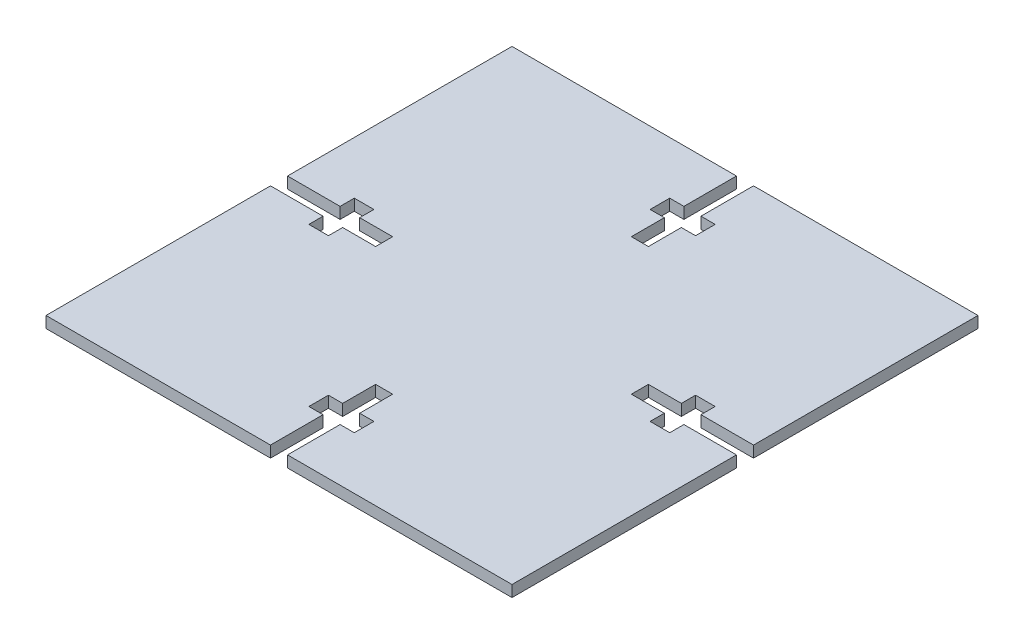
SolidWorks part; units mm, degrees
ref_plane "Front Plane" through (0, 0, 0) normal (0, 0, 1) x (1, 0, 0)
ref_plane "Top Plane" through (0, 0, 0) normal (0, 1, 0) x (1, 0, 0)
ref_plane "Right Plane" through (0, 0, 0) normal (1, 0, 0) x (0, 0, -1)
sketch "Sketch1" plane through (0, 0, 0) normal (0, 1, 0) x (1, 0, 0)
  line L1 (-41, -41) -> (41, -41)
  line L2 (-41, -41) -> (-41, 41)
  line L3 (-41, 41) -> (41, 41)
  line L4 (41, -41) -> (41, 41)
  line L5 (-41, -41) -> (41, 41) construction
  line L6 (-41, 41) -> (41, -41) construction
  point P0 (0, 0)
  dimension "D1" = 82
  dimension "D2" = 82
extrude "Boss-Extrude1" add sketch "Sketch1" along normal blind 2
sketch "Sketch2" plane through (0, 0, 0) normal (0, -1, 0) x (-1, 0, 0)
  line L0 (0, 41) -> (0, -41) construction
  line L1 (-41, 41) -> (41, 41) construction
  line L2 (41, -41) -> (-41, -41) construction
  line L4 (-1.5, 22.5) -> (1.5, 22.5)
  line L5 (-1.5, 22.5) -> (-1.5, 28.3)
  line L6 (-1.5, 41) -> (1.5, 41)
  line L7 (1.5, 22.5) -> (1.5, 28.3)
  line L8 (-1.5, 22.5) -> (1.5, 41) construction
  line L9 (-1.5, 41) -> (1.5, 22.5) construction
  line L10 (4, 28.3) -> (1.5, 28.3)
  line L11 (4, 28.3) -> (4, 31.75)
  line L12 (4, 31.75) -> (1.5, 31.75)
  line L13 (-4, 28.3) -> (-4, 31.75)
  line L14 (4, 28.3) -> (-4, 31.75) construction
  line L15 (4, 31.75) -> (-4, 28.3) construction
  line L39 (1.5, 31.75) -> (1.5, 41)
  line L40 (-1.5, 31.75) -> (-4, 31.75)
  line L41 (-1.5, 31.75) -> (-1.5, 41)
  line L42 (-1.5, 28.3) -> (-4, 28.3)
  line L43 (28.3, -4) -> (28.3, -1.5)
  line L44 (22.5, -1.5) -> (28.3, -1.5)
  line L45 (22.5, 1.5) -> (22.5, -1.5)
  line L46 (22.5, 1.5) -> (28.3, 1.5)
  line L47 (28.3, 1.5) -> (28.3, 4)
  line L48 (28.3, 4) -> (31.75, 4)
  line L49 (31.75, 1.5) -> (31.75, 4)
  line L50 (31.75, 1.5) -> (41, 1.5)
  line L51 (41, 1.5) -> (41, -1.5)
  line L52 (31.75, -1.5) -> (41, -1.5)
  line L53 (31.75, -4) -> (31.75, -1.5)
  line L54 (28.3, -4) -> (31.75, -4)
  line L55 (-4, -28.3) -> (-1.5, -28.3)
  line L56 (-1.5, -22.5) -> (-1.5, -28.3)
  line L57 (1.5, -22.5) -> (-1.5, -22.5)
  line L58 (1.5, -22.5) -> (1.5, -28.3)
  line L59 (1.5, -28.3) -> (4, -28.3)
  line L60 (4, -28.3) -> (4, -31.75)
  line L61 (1.5, -31.75) -> (4, -31.75)
  line L62 (1.5, -31.75) -> (1.5, -41)
  line L63 (1.5, -41) -> (-1.5, -41)
  line L64 (-1.5, -31.75) -> (-1.5, -41)
  line L65 (-4, -31.75) -> (-1.5, -31.75)
  line L66 (-4, -28.3) -> (-4, -31.75)
  line L67 (-28.3, 4) -> (-28.3, 1.5)
  line L68 (-22.5, 1.5) -> (-28.3, 1.5)
  line L69 (-22.5, -1.5) -> (-22.5, 1.5)
  line L70 (-22.5, -1.5) -> (-28.3, -1.5)
  line L71 (-28.3, -1.5) -> (-28.3, -4)
  line L72 (-28.3, -4) -> (-31.75, -4)
  line L73 (-31.75, -1.5) -> (-31.75, -4)
  line L74 (-31.75, -1.5) -> (-41, -1.5)
  line L75 (-41, -1.5) -> (-41, 1.5)
  line L76 (-31.75, 1.5) -> (-41, 1.5)
  line L77 (-31.75, 4) -> (-31.75, 1.5)
  line L78 (-28.3, 4) -> (-31.75, 4)
  point P6 (0, 31.75)
  point P11 (0, 30.025)
  point P59 (0, 0)
  dimension "D1" = 18.5
  dimension "D2" = 3
  dimension "D3" = 2.5
  dimension "D4" = 3.45
  dimension "D5" = 5.8
  dimension "D6" = 4
extrude "Cut-Extrude2" cut sketch "Sketch2" against normal blind 10
